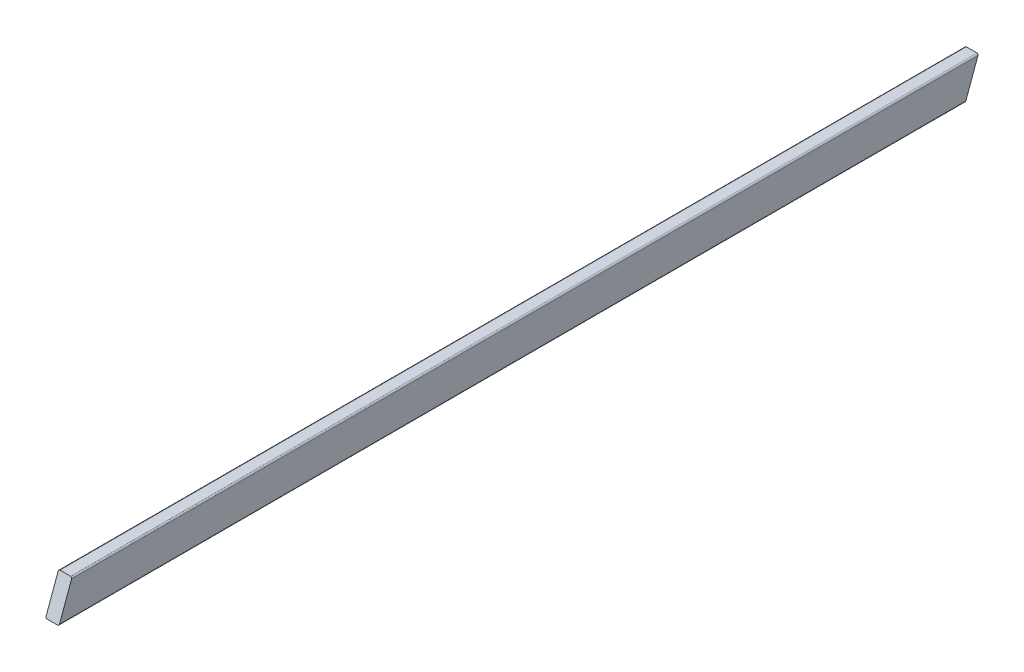
SolidWorks part; units mm, degrees
ref_plane "Front Plane" through (0, 0, 0) normal (0, 0, 1) x (1, 0, 0)
ref_plane "Top Plane" through (0, 0, 0) normal (0, 1, 0) x (1, 0, 0)
ref_plane "Right Plane" through (0, 0, 0) normal (1, 0, 0) x (0, 0, -1)
sketch "Esboço1" plane through (0, 0, 0) normal (0, 0, 1) x (1, 0, 0)
  line L1 (-4.7625, -12.7) -> (4.7625, -12.7)
  line L2 (-4.7625, -12.7) -> (-4.7625, 12.7)
  line L3 (-4.7625, 12.7) -> (4.7625, 12.7)
  line L4 (4.7625, -12.7) -> (4.7625, 12.7)
  line L5 (-4.7625, -12.7) -> (4.7625, 12.7) construction
  line L6 (-4.7625, 12.7) -> (4.7625, -12.7) construction
  point P0 (0, 0)
  dimension "D1" = 9.525
  dimension "D2" = 25.4
extrude "Ressalto-extrusão1" add sketch "Esboço1" along normal mid plane 800
sketch "Esboço3" plane through (4.7625, 0, 0) normal (1, 0, 0) x (0, 0, -1)
  line L0 (-326.1265, -12.7) -> (316.8816, -12.7)
  line L1 (-326.1265, -12.7) -> (-316.8816, 12.7)
  line L2 (316.8816, -12.7) -> (326.1265, 12.7)
  line L3 (-316.8816, 12.7) -> (326.1265, 12.7)
  line L4 (-400, 12.7) -> (400, 12.7) construction
  line L5 (-400, -12.7) -> (400, -12.7) construction
  line L6 (-321.5041, 0) -> (321.5041, 0) construction
  line L7 (-400, -12.7) -> (-400, 12.7) construction
  point P10 (0, 0)
  dimension "D1" = 20
  dimension "D2" = 604.23
extrude "Corte-extrusão2" cut sketch "Esboço3" against normal through all flip side to cut
fillet "Filete1" radius 1 4 edges at (-4.7625, -12.7, 4.6224) (4.7625, -12.7, 4.6224) (-4.7625, 12.7, -4.6224) (4.7625, 12.7, -4.6224)
sketch "Esboço4" plane through (4.7625, 0, 0) normal (1, 0, 0) x (0, 0, -1)
  line L0 (326.1265, 12.7) -> (353.1566, 12.7)
  line L1 (353.1566, 12.7) -> (343.9118, -12.7)
  line L2 (343.9118, -12.7) -> (316.8816, -12.7)
  line L3 (-316.8816, 12.7) -> (-343.9118, 12.7)
  line L4 (-343.9118, 12.7) -> (-353.1566, -12.7)
  line L5 (-353.1566, -12.7) -> (-326.1265, -12.7)
  line L6 (-317.2456, 11.7) -> (-325.7625, -11.7) construction
  line L8 (317.2456, -11.7) -> (325.7625, 11.7) construction
  dimension "D1" = 25.4
  dimension "D2" = 25.4
